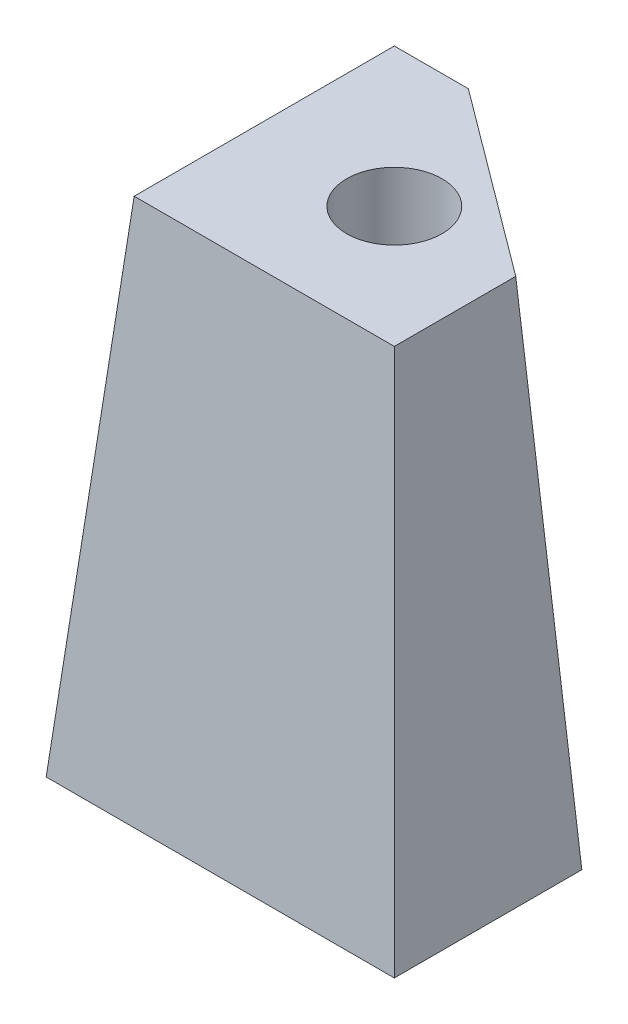
SolidWorks part; units mm, degrees
ref_plane "Front Plane" through (0, 0, 0) normal (0, 0, 1) x (1, 0, 0)
ref_plane "Top Plane" through (0, 0, 0) normal (0, 1, 0) x (1, 0, 0)
ref_plane "Right Plane" through (0, 0, 0) normal (1, 0, 0) x (0, 0, -1)
sketch "Sketch1" plane through (0, 0, 0) normal (0, 1, 0) x (1, 0, 0)
  line L3 (10.4204, -7.2013) -> (-4.5796, -7.2013)
  line L5 (-4.5796, -7.2013) -> (-4.5796, 7.7987)
  line L6 (-4.5796, 7.7987) -> (-0.3125, 7.7987)
  line L7 (-0.3125, 7.7987) -> (10.4204, -0.2013)
  line L8 (10.4204, -0.2013) -> (10.4204, -7.2013)
  dimension "D1" = 15
  dimension "D2" = 15
  dimension "D3" = 7
  dimension "D4" = 126.7
extrude "Boss-Extrude1" add sketch "Sketch1" along normal blind 29
sketch "Sketch2" plane through (0, 0, 0) normal (0, -1, 0) x (1, 0, 0)
  line L1 (10.4204, 7.2013) -> (10.4204, 0.2013) construction
  line L2 (-4.5796, 7.2013) -> (10.4204, 7.2013) construction
  line L3 (-4.5796, -7.7987) -> (-4.5796, 7.2013) construction
  circle A0 centre (-0.5796, 2.2013) radius 2
  circle A1 centre (7.4204, 2.2013) radius 1.5
  dimension "D1" = 4
  dimension "D3" = 3
  dimension "D2" = 4
  dimension "D4" = 3
  dimension "D5" = 5
  dimension "D6" = 5
extrude "Cut-Extrude1" cut sketch "Sketch2" against normal blind 10
sketch "Sketch3" plane through (0, 29, 0) normal (0, 1, 0) x (1, 0, 0)
  line L0 (10.4204, -7.2013) -> (10.4204, -0.2013) construction
  line L1 (-4.5796, -7.2013) -> (10.4204, -7.2013) construction
  circle A0 centre (3.4204, -0.2013) radius 2.75
  dimension "D1" = 5.5
  dimension "D2" = 7
  dimension "D3" = 7
extrude "Cut-Extrude2" cut sketch "Sketch3" against normal blind 6
draft "Draft1" type of draft neutral plane draft angle 5 faces to draft 5 face at (5.0539, 14.5, -3.7987) face at (-2.4461, 14.5, -7.7987) face at (-4.5796, 14.5, -0.2987) face at (10.4204, 14.5, 3.7013) face at (2.9204, 14.5, 7.2013) neutral plane through (0, 29, 0) neutral plane normal (0, 1, 0) parameters "D1"=5
